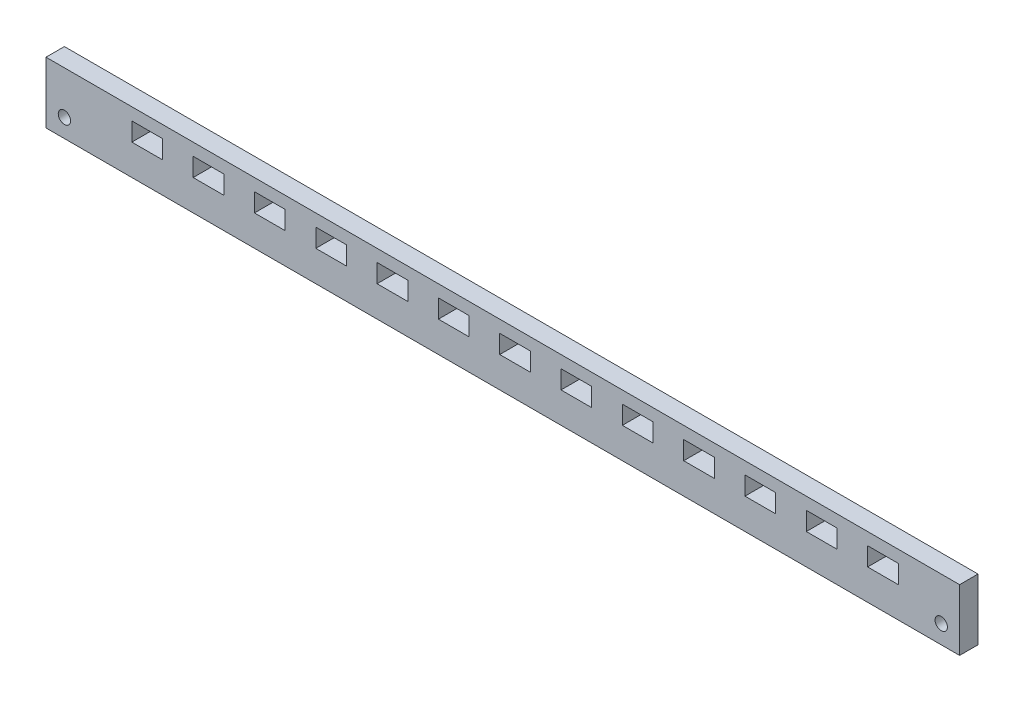
SolidWorks part; units mm, degrees
ref_plane "Plan de face" through (0, 0, 0) normal (0, 0, 1) x (1, 0, 0)
ref_plane "Plan de dessus" through (0, 0, 0) normal (0, 1, 0) x (1, 0, 0)
ref_plane "Plan de droite" through (0, 0, 0) normal (1, 0, 0) x (0, 0, -1)
sketch "Esquisse1" plane through (0, 0, 0) normal (0, 0, 1) x (1, 0, 0)
  line L1 (0, 0) -> (149, 0)
  line L2 (0, 0) -> (0, 10)
  line L3 (0, 10) -> (149, 10)
  line L4 (149, 0) -> (149, 10)
  dimension "D1" = 10
  dimension "D2" = 149
extrude "Boss.-Extru.1" add sketch "Esquisse1" along normal blind 3
sketch "Esquisse2" plane through (0, 0, 0) normal (0, 0, -1) x (-1, 0, 0)
  line L0 (0, 0) -> (-149, 0) construction
  line L1 (-149, 10) -> (0, 10) construction
  line L2 (-139, 8) -> (-134, 8)
  line L3 (-139, 8) -> (-139, 5)
  line L4 (-139, 5) -> (-134, 5)
  line L5 (-149, 0) -> (-149, 10) construction
  line L6 (0, 10) -> (0, 0) construction
  line L8 (-134, 8) -> (-134, 5)
  line L9 (-129, 8) -> (-124, 8)
  line L10 (-129, 8) -> (-129, 5)
  line L11 (-129, 5) -> (-124, 5)
  line L12 (-124, 8) -> (-124, 5)
  line L13 (-119, 8) -> (-114, 8)
  line L14 (-119, 8) -> (-119, 5)
  line L15 (-119, 5) -> (-114, 5)
  line L16 (-114, 8) -> (-114, 5)
  line L17 (-109, 8) -> (-104, 8)
  line L18 (-109, 8) -> (-109, 5)
  line L19 (-109, 5) -> (-104, 5)
  line L20 (-104, 8) -> (-104, 5)
  line L21 (-99, 8) -> (-94, 8)
  line L22 (-99, 8) -> (-99, 5)
  line L23 (-99, 5) -> (-94, 5)
  line L24 (-94, 8) -> (-94, 5)
  line L25 (-89, 8) -> (-84, 8)
  line L26 (-89, 8) -> (-89, 5)
  line L27 (-89, 5) -> (-84, 5)
  line L28 (-84, 8) -> (-84, 5)
  line L29 (-79, 8) -> (-74, 8)
  line L30 (-79, 8) -> (-79, 5)
  line L31 (-79, 5) -> (-74, 5)
  line L32 (-74, 8) -> (-74, 5)
  line L33 (-69, 8) -> (-64, 8)
  line L34 (-69, 8) -> (-69, 5)
  line L35 (-69, 5) -> (-64, 5)
  line L36 (-64, 8) -> (-64, 5)
  line L37 (-59, 8) -> (-54, 8)
  line L38 (-59, 8) -> (-59, 5)
  line L39 (-59, 5) -> (-54, 5)
  line L40 (-54, 8) -> (-54, 5)
  line L41 (-49, 8) -> (-44, 8)
  line L42 (-49, 8) -> (-49, 5)
  line L43 (-49, 5) -> (-44, 5)
  line L44 (-44, 8) -> (-44, 5)
  line L45 (-39, 8) -> (-34, 8)
  line L46 (-39, 8) -> (-39, 5)
  line L47 (-39, 5) -> (-34, 5)
  line L48 (-34, 8) -> (-34, 5)
  line L49 (-29, 8) -> (-24, 8)
  line L50 (-29, 8) -> (-29, 5)
  line L51 (-29, 5) -> (-24, 5)
  line L52 (-24, 8) -> (-24, 5)
  line L53 (-19, 8) -> (-14, 8)
  line L54 (-19, 8) -> (-19, 5)
  line L55 (-19, 5) -> (-14, 5)
  line L56 (-14, 8) -> (-14, 5)
  line L61 (-9, 8) -> (-4, 8) [skipped]
  line L62 (-9, 8) -> (-9, 5) [skipped]
  line L63 (-9, 5) -> (-4, 5) [skipped]
  line L64 (-4, 8) -> (-4, 5) [skipped]
  circle A0 centre (-3, 3) radius 1.005
  circle A1 centre (-146, 3) radius 1.005
  dimension "D1" = 2.01
  dimension "D2" = 2.01
  dimension "D3" = 3
  dimension "D4" = 3
  dimension "D5" = 5
  dimension "D6" = 3
  dimension "D9" = 3
  dimension "D13" = 3
  dimension "D7" = 10
  dimension "D8" = 2
  dimension "D10" = 14
  dimension "D11" = 2
  dimension "D12" = 5
extrude "Enlèv. mat.-Extru.1" cut sketch "Esquisse2" against normal through all
